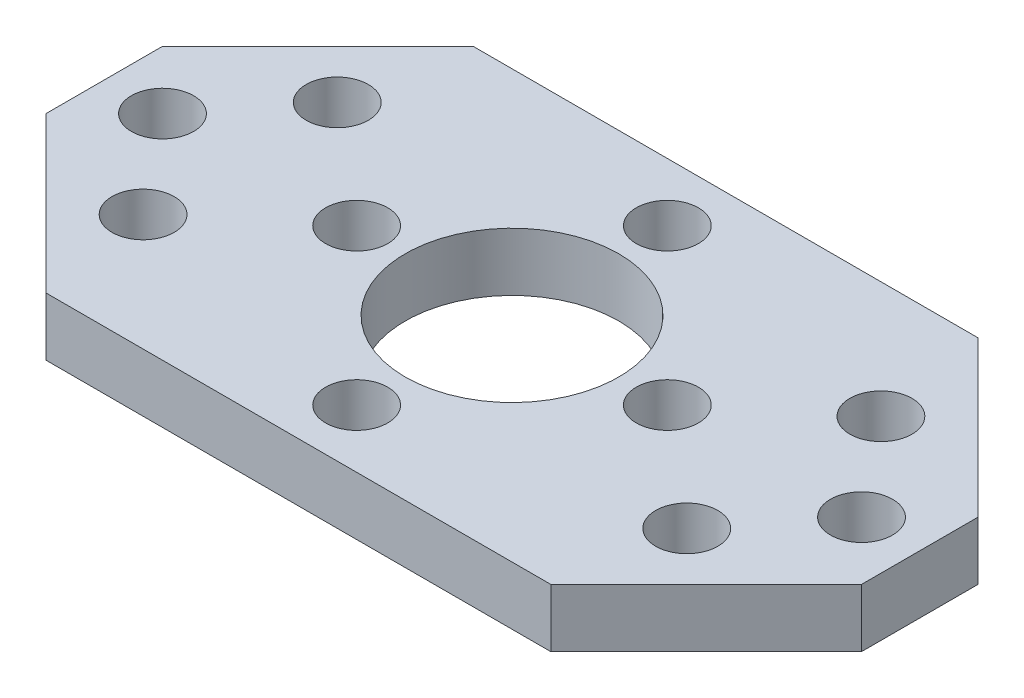
SolidWorks part; units mm, degrees
material "玻"
ref_plane "前视基准面" through (0, 0, 0) normal (0, 0, 1) x (1, 0, 0)
ref_plane "上视基准面" through (0, 0, 0) normal (0, 1, 0) x (1, 0, 0)
ref_plane "右视基准面" through (0, 0, 0) normal (1, 0, 0) x (0, 0, -1)
sketch "草图1" plane through (0, 0, 0) normal (0, 1, 0) x (1, 0, 0)
  line L0 (0, 0) -> (25.2004, 0) construction
  line L1 (0, 0) -> (0, 32.3199) construction
  line L7 (-21, 3) -> (-13, 11)
  line L8 (-13, -11) -> (13, -11)
  line L9 (-21, -3) -> (-21, 3)
  line L10 (-13, 11) -> (13, 11)
  line L11 (21, -3) -> (21, 3)
  line L12 (-21, -11) -> (21, 11) construction
  line L13 (-21, 11) -> (21, -11) construction
  line L14 (-21, -3) -> (-13, -11)
  line L15 (13, -11) -> (21, -3)
  line L16 (13, 11) -> (21, 3)
  circle A0 centre (0, 0) radius 11 construction
  circle A1 centre (0, 8) radius 1.6
  circle A3 centre (8, 0) radius 1.6
  circle A4 centre (-8, 0) radius 1.6
  circle A15 centre (0, 0) radius 5.5
  circle A16 centre (0, -8) radius 1.6
  circle A17 centre (-18, 0) radius 1.6
  circle A18 centre (-14, 5) radius 1.6
  circle A19 centre (-14, -5) radius 1.6
  circle A20 centre (14, -5) radius 1.6
  circle A21 centre (18, 0) radius 1.6
  circle A22 centre (14, 5) radius 1.6
  dimension "D2" = 3.2
  dimension "D3" = 8
  dimension "D4" = 3.2
  dimension "D5" = 8
  dimension "D8" = 42
  dimension "D9" = 3.2
  dimension "D10" = 3
  dimension "D14" = 11
  dimension "D15" = 11
  dimension "D16" = 3.2
  dimension "D6" = 22
  dimension "D17" = 7
  dimension "D18" = 6
  dimension "D7" = 22
extrude "凸台-拉伸1" add sketch "草图1" along normal blind 3
